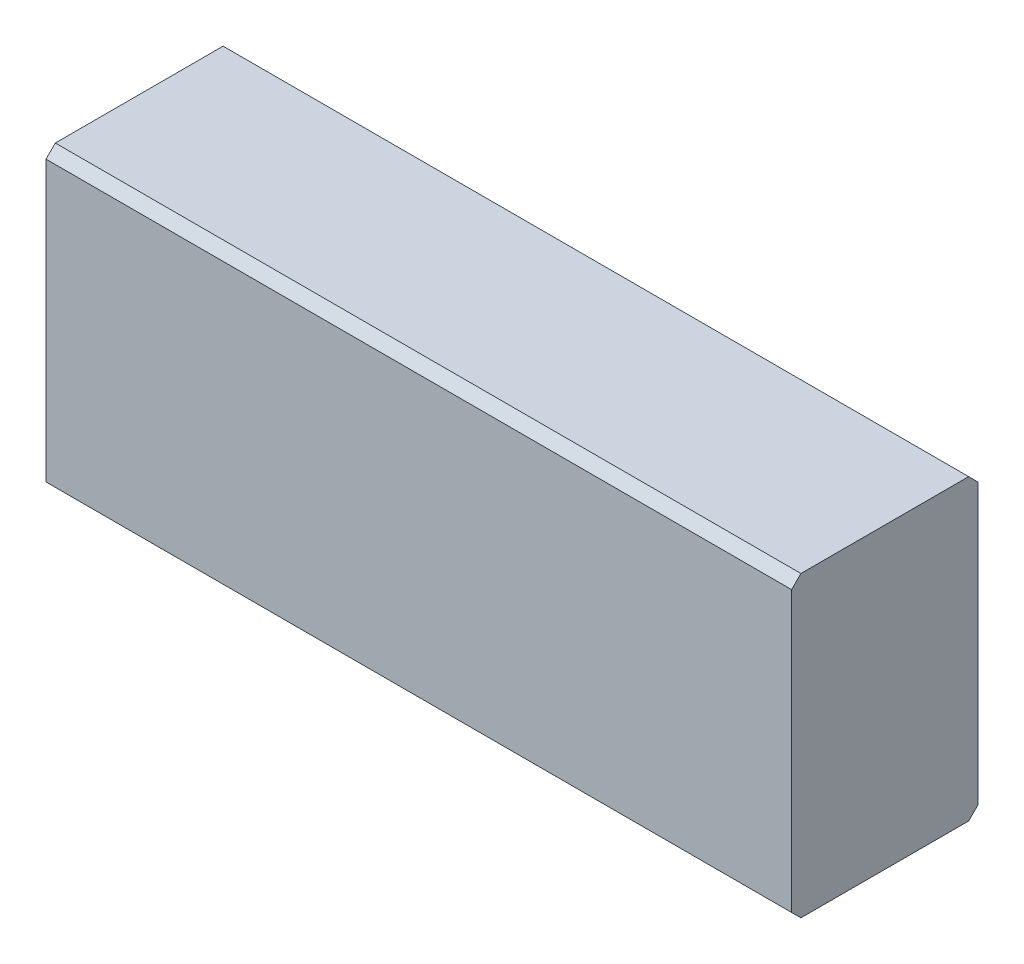
SolidWorks part; units mm, degrees
ref_plane "Front" through (0, 0, 0) normal (0, 0, 1) x (1, 0, 0)
ref_plane "Top" through (0, 0, 0) normal (0, 1, 0) x (1, 0, 0)
ref_plane "Right" through (0, 0, 0) normal (1, 0, 0) x (0, 0, -1)
other "Configuration Table"
sketch "Sketch1" plane through (0, 0, 0) normal (0, 0, 1) x (1, 0, 0)
  line L0 (0, 4) -> (-12, 4)
  line L1 (-12, -4) -> (0, -4)
  arc A0 (-12, 4) -> (-12, -4) centre (-12, 0) ccw
  arc A1 (0, -4) -> (0, 4) centre (0, 0) ccw
  dimension "b" = 8
  dimension "l" = 20
extrude "Extrude1" add sketch "Sketch1" along normal blind 5
sketch "Sketch2" plane through (0, 0, 0) normal (0, 0, 1) x (1, 0, 0)
  line L0 (0, 4) -> (-12, 4) construction
  line L1 (-16, 4) -> (4, 4)
  line L2 (-16, 4) -> (-16, -4)
  line L3 (-16, -4) -> (4, -4)
  line L4 (4, 4) -> (4, -4)
  line L5 (-12, -4) -> (0, -4) construction
  arc A0 (-12, 4) -> (-12, -4) centre (-12, 0) ccw construction
  arc A1 (0, -4) -> (0, 4) centre (0, 0) ccw construction
extrude "Extrude2" add sketch "Sketch2" along normal blind 5
sketch "Sketch3" plane through (0, 0, 0) normal (0, 0, 1) x (1, 0, 0)
  line L0 (-12, -4) -> (0, -4) construction
  line L1 (-12, -4) -> (4, -4)
  line L3 (-12, 4) -> (4, 4)
  line L4 (4, -4) -> (4, 4)
  arc A1 (-12, 4) -> (-12, -4) centre (-12, 0) ccw
  arc A2 (0, -4) -> (0, 4) centre (0, 0) ccw construction
  arc A3 (-12, 4) -> (-12, -4) centre (-12, 0) ccw construction
extrude "Extrude3" [suppressed] add sketch "Sketch3" along normal blind 5
chamfer "Chamfer1" distance 0.25 angle 45 8 edges at (-6, 4, 0) (-6, -4, 0) (-6, 4, 5) (-6, -4, 5) (4, 0, 0) (-16, 0, 0) (4, 0, 5) (-16, 0, 5)
equation "\"D1@Extrude2\" = \"h@Extrude1\""
equation "\"D1@Extrude3\" = \"h@Extrude1\""
